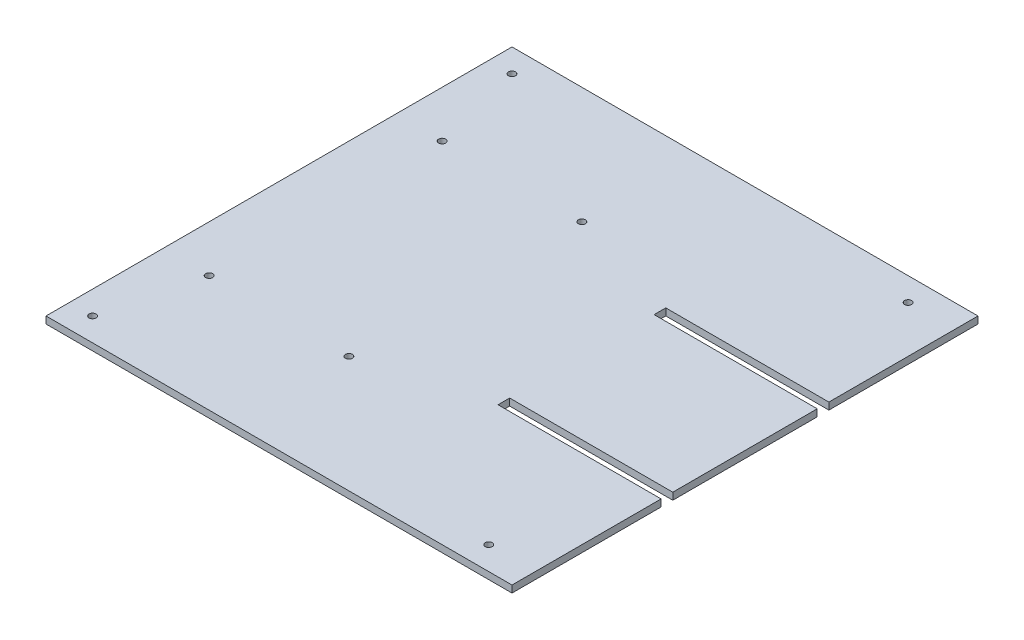
SolidWorks part; units mm, degrees
material "Acrylic (Medium-high impact)"
ref_plane "Front Plane" through (0, 0, 0) normal (0, 0, 1) x (1, 0, 0)
ref_plane "Top Plane" through (0, 0, 0) normal (0, 1, 0) x (1, 0, 0)
ref_plane "Right Plane" through (0, 0, 0) normal (1, 0, 0) x (0, 0, -1)
sketch "Sketch1" plane through (0, 0, 0) normal (0, 1, 0) x (1, 0, 0)
  line L1 (100, -100) -> (-100, -100)
  line L2 (100, -100) -> (100, 100)
  line L3 (100, 100) -> (-100, 100)
  line L4 (-100, -100) -> (-100, 100)
  line L5 (100, -100) -> (-100, 100) construction
  line L6 (100, 100) -> (-100, -100) construction
  point P0 (0, 0)
  dimension "D1" = 200
  dimension "D2" = 200
extrude "Boss-Extrude1" add sketch "Sketch1" along normal blind 3
sketch "Sketch2" plane through (0, 3, 0) normal (0, 1, 0) x (1, 0, 0)
  line L0 (-100, -100) -> (100, -100) construction
  line L1 (-100, 100) -> (-100, -100) construction
  line L2 (100, -100) -> (100, 100) construction
  line L3 (-100, 0) -> (100, 0) construction
  circle A0 centre (-90, -90) radius 1.5
  circle A1 centre (80, -90) radius 1.5
  circle A2 centre (80, 90) radius 1.5
  circle A3 centre (-90, 90) radius 1.5
  dimension "D1" = 3
  dimension "D4" = 3
  dimension "D2" = 10
  dimension "D3" = 10
  dimension "D5" = 20
  dimension "D6" = 10
extrude "Cut-Extrude1" cut sketch "Sketch2" against normal blind 3
sketch "Sketch3" plane through (0, 3, 0) normal (0, 1, 0) x (1, 0, 0)
  line L0 (100, -36) -> (30, -36)
  line L1 (100, -100) -> (100, 100) construction
  line L2 (30, -36) -> (30, -31)
  line L3 (30, -31) -> (100, -31)
  line L4 (100, -31) -> (100, -36)
  line L5 (-100, -100) -> (100, -100) construction
  line L6 (100, 36) -> (30, 36)
  line L7 (30, 36) -> (30, 31)
  line L8 (30, 31) -> (100, 31)
  line L9 (100, 31) -> (100, 36)
  line L10 (100, 100) -> (-100, 100) construction
  dimension "D1" = 70
  dimension "D2" = 5
  dimension "D3" = 64
  dimension "D4" = 70
  dimension "D5" = 5
  dimension "D6" = 64
extrude "Cut-Extrude2" cut sketch "Sketch3" against normal blind 3
sketch "Sketch4" plane through (0, 3, 0) normal (0, 1, 0) x (1, 0, 0)
  line L0 (-100, 100) -> (-100, -100) construction
  line L1 (-100, -100) -> (100, -100) construction
  line L2 (-100, 0) -> (0, 0) construction
  circle A0 centre (-80, -50) radius 1.5
  circle A1 centre (-20, -50) radius 1.5
  circle A2 centre (-80, 50) radius 1.5
  circle A3 centre (-20, 50) radius 1.5
  dimension "D1" = 3
  dimension "D4" = 3
  dimension "D7" = 3
  dimension "D10" = 3
  dimension "D2" = 20
  dimension "D3" = 50
  dimension "D5" = 60
  dimension "D6" = 50
  dimension "D8" = 100
  dimension "D9" = 100
  dimension "D11" = 60
  dimension "D12" = 60
extrude "Cut-Extrude5" cut sketch "Sketch4" against normal blind 3
